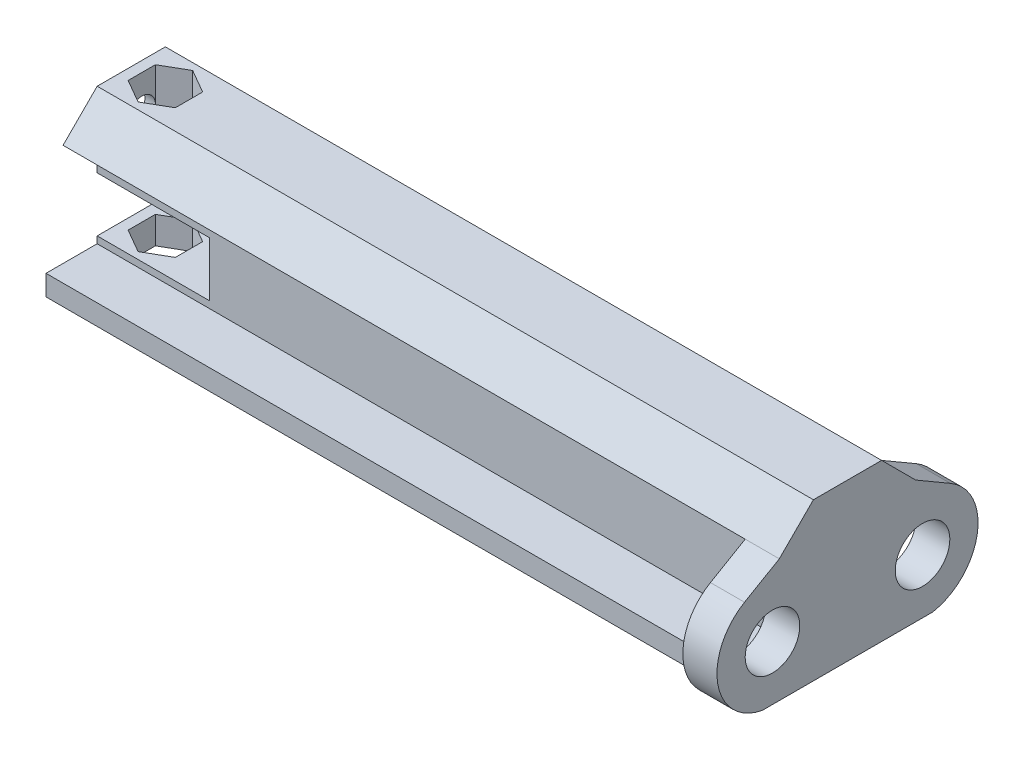
SolidWorks part; units mm, degrees
ref_plane "Front Plane" through (0, 0, 0) normal (0, 0, 1) x (1, 0, 0)
ref_plane "Top Plane" through (0, 0, 0) normal (0, 1, 0) x (1, 0, 0)
ref_plane "Right Plane" through (0, 0, 0) normal (1, 0, 0) x (0, 0, -1)
sketch "Sketch1" plane through (0, 0, 0) normal (1, 0, 0) x (0, 0, -1)
  line L0 (5, 5) -> (10, 10)
  line L1 (-5, 5) -> (5, 5) construction
  line L2 (-5, 5) -> (-5, -5)
  line L3 (-5, -5) -> (5, -5) construction
  line L4 (5, 5) -> (5, -5)
  line L5 (-5, 5) -> (5, -5) construction
  line L6 (-5, -5) -> (5, 5) construction
  line L7 (10, 10) -> (5, 15)
  line L8 (5, 15) -> (-5, 15)
  line L9 (-5, 15) -> (-10, 10)
  line L10 (-10, 10) -> (-5, 5)
  line L11 (5, -5) -> (12.5, -5)
  line L12 (12.5, -5) -> (12.5, -8)
  line L13 (-5, -5) -> (-12.5, -5)
  line L14 (-12.5, -5) -> (-12.5, -8)
  line L15 (-12.5, -8) -> (12.5, -8)
  point P0 (0, 0)
  dimension "D1" = 10
  dimension "D2" = 10
  dimension "D3" = 7.5
  dimension "D4" = 3
  dimension "D5" = 7.5
extrude "Boss-Extrude1" add sketch "Sketch1" along normal mid plane 100
sketch "Sketch2" plane through (0, 0, 0) normal (0, 1, 0) x (1, 0, 0)
  line L0 (0, 0) -> (-45, 0) construction
  circle A0 centre (-45, 0) radius 12.5
  circle A1 centre (-45, 0) radius 4
  dimension "D2" = 25
  dimension "D3" = 8
  dimension "D1" = 45
extrude "Cut-Extrude1" cut sketch "Sketch2" against normal mid plane 8
sketch "Sketch4" plane through (0, 0, 0) normal (0, 1, 0) x (1, 0, 0)
  line L0 (0, 0) -> (-45, 0) construction
  line L2 (-45, -4) -> (-41.5359, -2)
  line L3 (-41.5359, -2) -> (-41.5359, 2)
  line L4 (-41.5359, 2) -> (-45, 4)
  line L5 (-45, 4) -> (-48.4641, 2)
  line L6 (-48.4641, 2) -> (-48.4641, -2)
  line L7 (-48.4641, -2) -> (-45, -4)
  circle A0 centre (-45, 0) radius 4 construction
  dimension "D2" = 8
  dimension "D1" = 45
extrude "Cut-Extrude3" cut sketch "Sketch4" against normal through all both and the other way through all
sketch "Sketch6" plane through (-50, 0, 0) normal (-1, 0, 0) x (0, 0, 1)
  line L0 (0, 15) -> (0, 10) construction
  line L1 (-5, 15) -> (5, 15) construction
  circle A0 centre (0, 10) radius 2
  dimension "D2" = 4
  dimension "D1" = 5
extrude "Cut-Extrude4" cut sketch "Sketch6" against normal blind 4
sketch "Sketch7" plane through (50, 0, 0) normal (1, 0, 0) x (0, 0, -1)
  line L0 (0, 12.65) -> (0, -12.65) construction
  line L1 (10, 10) -> (15.0947, 7.0345)
  line L3 (-10, 10) -> (-15.0947, 7.0345)
  line L4 (-12.5, -8) -> (12.5, -8)
  line L6 (-10, 10) -> (-5, 15)
  line L7 (-5, 15) -> (5, 15)
  line L8 (5, 15) -> (10, 10)
  circle A0 centre (11, 0) radius 4
  circle A1 centre (-11, 0) radius 4
  arc A2 (15.0947, 7.0345) -> (12.5, -8) centre (11, 0) cw
  arc A3 (-15.0947, 7.0345) -> (-12.5, -8) centre (-11, 0) ccw
  dimension "D1" = 8
  dimension "D2" = 11
extrude "Boss-Extrude3" add sketch "Sketch7" along normal blind 5
